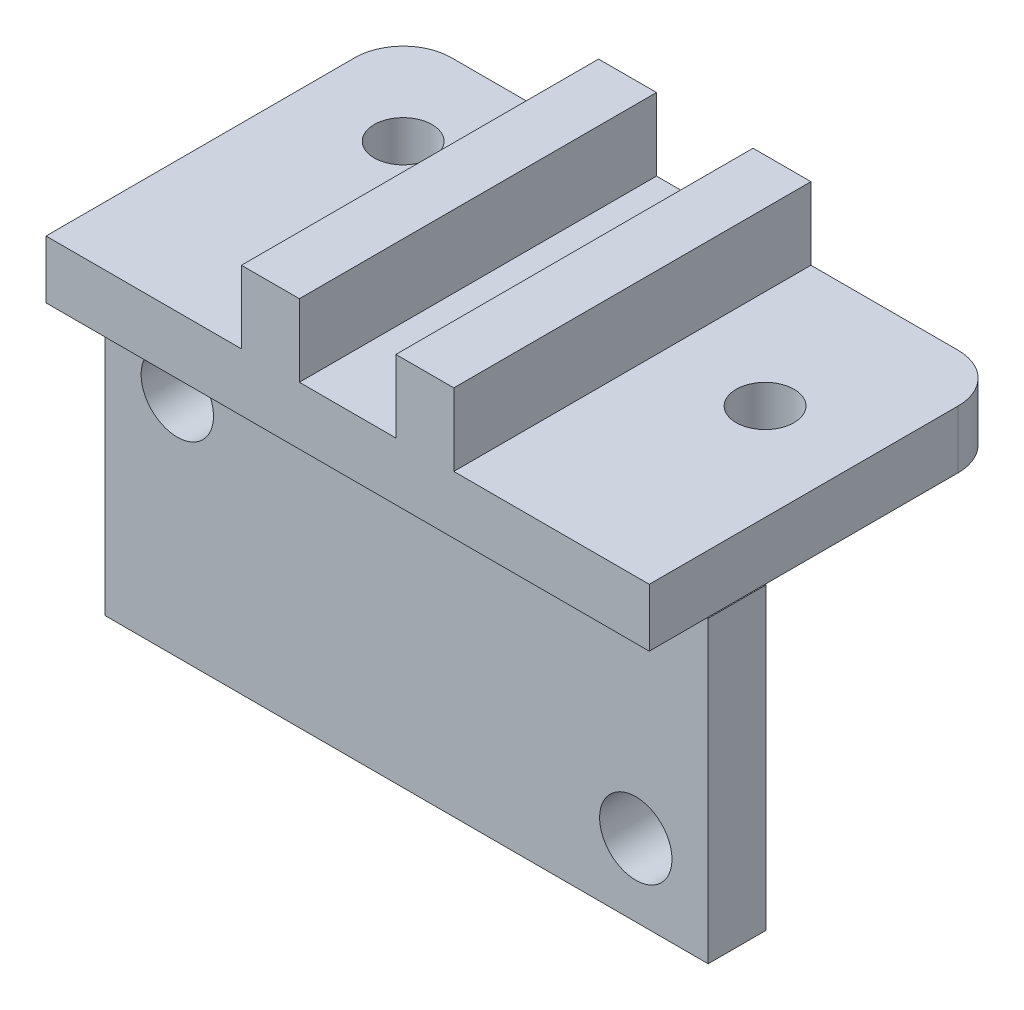
SolidWorks part; units mm, degrees
ref_plane "Front Plane" through (0, 0, 0) normal (0, 0, 1) x (1, 0, 0)
ref_plane "Top Plane" through (0, 0, 0) normal (0, 1, 0) x (1, 0, 0)
ref_plane "Right Plane" through (0, 0, 0) normal (1, 0, 0) x (0, 0, -1)
sketch "Sketch1" plane through (0, 0, 0) normal (0, 0, 1) x (1, 0, 0)
  line L0 (0, 0) -> (59630.2386, 0) construction
  line L2 (-13.6148, 0) -> (111.3852, 0)
  line L3 (-13.6148, 0) -> (-13.6148, -62)
  line L4 (-13.6148, -62) -> (111.3852, -62)
  line L5 (111.3852, 0) -> (111.3852, -62)
  dimension "D1" = 125
  dimension "D2" = 62
extrude "Boss-Extrude1" add sketch "Sketch1" along normal blind 12 from offset 0 contours L3 L2 L5 L4
sketch "Sketch2" plane through (0, 0, 0) normal (0, 0, 1) x (1, 0, 0)
  line L0 (111.3852, 0) -> (111.3852, -62) construction
  line L2 (-13.6148, 0) -> (111.3852, 0) construction
  line L3 (-13.6148, -62) -> (111.3852, -62) construction
  line L5 (-13.6148, 0) -> (-13.6148, -62) construction
  circle A0 centre (1.3852, -47) radius 7.5
  circle A1 centre (96.3852, -15) radius 7.5
  point P8 (93.1565, 0)
  point P13 (-13.6148, -49.4306)
  dimension "D3" = 15
  dimension "D6" = 15
  dimension "D1" = 15
  dimension "D2" = 15
  dimension "D4" = 15
  dimension "D5" = 15
sketch "Sketch5" plane through (0, 0, 0) normal (0, 1, 0) x (1, 0, 0)
  line L1 (-3.8191, 50) -> (101.1809, 50)
  line L2 (-13.8191, 40) -> (-13.8191, -24)
  line L3 (-13.8191, -24) -> (111.1809, -24)
  line L4 (111.1809, 40) -> (111.1809, -24)
  arc A0 (101.1809, 50) -> (111.1809, 40) centre (101.1809, 40) cw
  arc A1 (-3.8191, 50) -> (-13.8191, 40) centre (-3.8191, 40) ccw
  point P7 (111.1809, 50)
  dimension "D4" = 10
  dimension "D1" = 74
  dimension "D2" = 12
  dimension "D3" = 125
extrude "Boss-Extrude5" add sketch "Sketch5" along normal blind 12
sketch "Sketch6" plane through (0, 0, 0) normal (0, 0, -1) x (-1, 0, 0)
  line L0 (13.6148, 0) -> (13.6148, -62) construction
  line L1 (13.6148, 0) -> (-111.1809, 0) construction
  line L2 (13.6148, -62) -> (-111.3852, -62) construction
  line L3 (-111.3852, 0) -> (-111.3852, -62) construction
  circle A0 centre (-96.3852, -47) radius 7.5
  circle A1 centre (-1.3852, -15) radius 7.5
  dimension "D1" = 15
  dimension "D2" = 15
  dimension "D3" = 15
  dimension "D4" = 15
  dimension "D5" = 15
  dimension "D6" = 15
extrude "Cut-Extrude2" cut sketch "Sketch6" against normal blind 68
sketch "Sketch8" plane through (0, 12, 0) normal (0, 1, 0) x (1, 0, 0)
  line L0 (101.1809, 50) -> (-3.8191, 50) construction
  line L1 (26.6809, 50) -> (38.6809, 50)
  line L2 (26.6809, 50) -> (26.6809, -24)
  line L3 (26.6809, -24) -> (38.6809, -24)
  line L4 (38.6809, 50) -> (38.6809, -24)
  line L5 (-13.8191, -24) -> (111.1809, -24) construction
  line L7 (58.6809, 50) -> (70.6809, 50)
  line L8 (58.6809, 50) -> (58.6809, -24)
  line L9 (58.6809, -24) -> (70.6809, -24)
  line L10 (70.6809, 50) -> (70.6809, -24)
  point P12 (48.6809, 50)
  dimension "D1" = 12
  dimension "D2" = 12
  dimension "D3" = 10
  dimension "D4" = 10
extrude "Boss-Extrude6" add sketch "Sketch8" along normal blind 15
sketch "Sketch10" plane through (0, 0, 0) normal (0, -1, 0) x (1, 0, 0)
  line L0 (101.1809, -50) -> (-3.8191, -50) construction
  line L2 (-13.6148, 0) -> (111.1809, 0) construction
  line L3 (53.5466, -50) -> (41.5466, -50)
  line L4 (53.5466, -50) -> (53.5466, 0)
  line L5 (53.5466, 0) -> (41.5466, 0)
  line L6 (41.5466, -50) -> (41.5466, 0)
  point P10 (47.5466, -50)
  dimension "D1" = 6
extrude "Boss-Extrude7" add sketch "Sketch10" along normal up to vertex (62 mm away)
sketch "Sketch11" plane through (41.5466, 0, 0) normal (-1, 0, 0) x (0, 0, 1)
  line L0 (-35.7957, 0) -> (0, -62)
  line L1 (0, 0) -> (-50, 0) construction
  line L2 (0, -62) -> (-50, -62)
  line L3 (-50, -62) -> (-50, 0)
  line L4 (-50, 0) -> (-35.7957, 0)
  line L5 (0, -62) -> (0, 0) construction
  dimension "D1" = 30
  dimension "D2" = 35.7957
extrude "Cut-Extrude3" cut sketch "Sketch11" against normal blind 62
sketch "Sketch12" plane through (0, 0, 0) normal (0, -1, 0) x (1, 0, 0)
  line L0 (101.1809, -50) -> (-3.8191, -50) construction
  line L1 (111.1809, 0) -> (111.1809, -40) construction
  line L2 (-13.6148, 0) -> (41.5466, 0) construction
  line L3 (-13.8191, -40) -> (-13.8191, 24) construction
  circle A0 centre (6.1809, -30) radius 6
  circle A1 centre (91.1809, -20) radius 6
  dimension "D2" = 12
  dimension "D4" = 12
  dimension "D1" = 30
  dimension "D3" = 20
  dimension "D5" = 30
  dimension "D6" = 20
extrude "Cut-Extrude4" cut sketch "Sketch12" against normal blind 62
